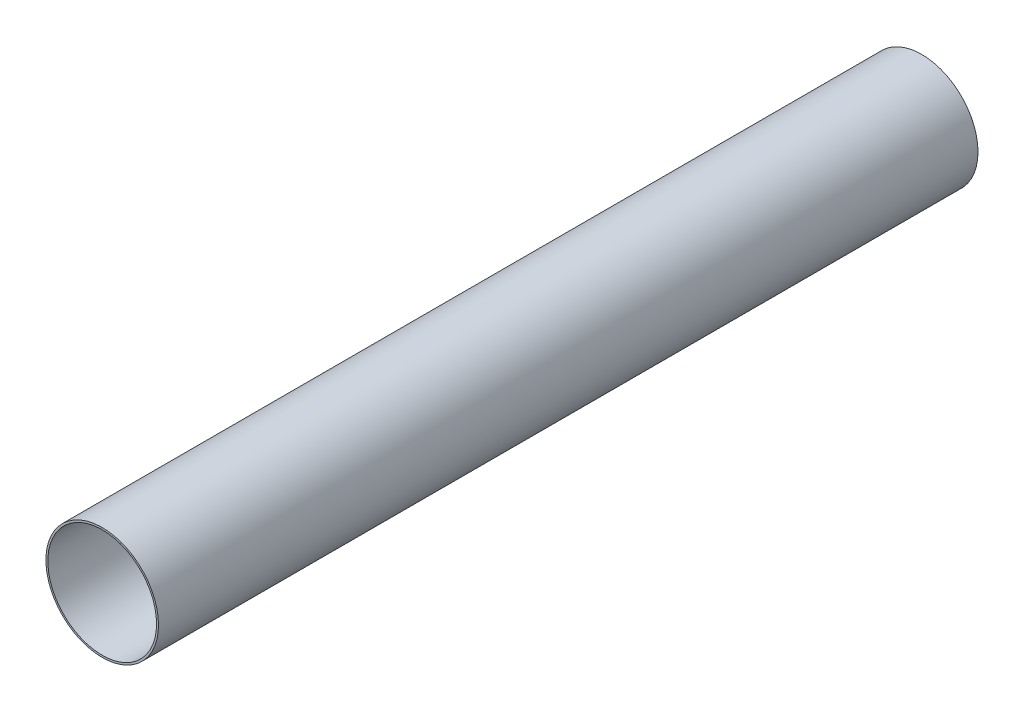
SolidWorks part; units mm, degrees
ref_plane "Plan de face" through (0, 0, 0) normal (0, 0, 1) x (1, 0, 0)
ref_plane "Plan de dessus" through (0, 0, 0) normal (0, 1, 0) x (1, 0, 0)
ref_plane "Plan de droite" through (0, 0, 0) normal (1, 0, 0) x (0, 0, -1)
sketch "Esquisse1" plane through (0, 0, 0) normal (0, 0, 1) x (1, 0, 0)
  circle A2 centre (0, 0) radius 79
  circle A3 centre (0, 0) radius 76.29
  dimension "D1" = 152.58
  dimension "D2" = 158
extrude "Boss.-Extru.1" add sketch "Esquisse1" along normal blind 1150 contours A2 | A3
